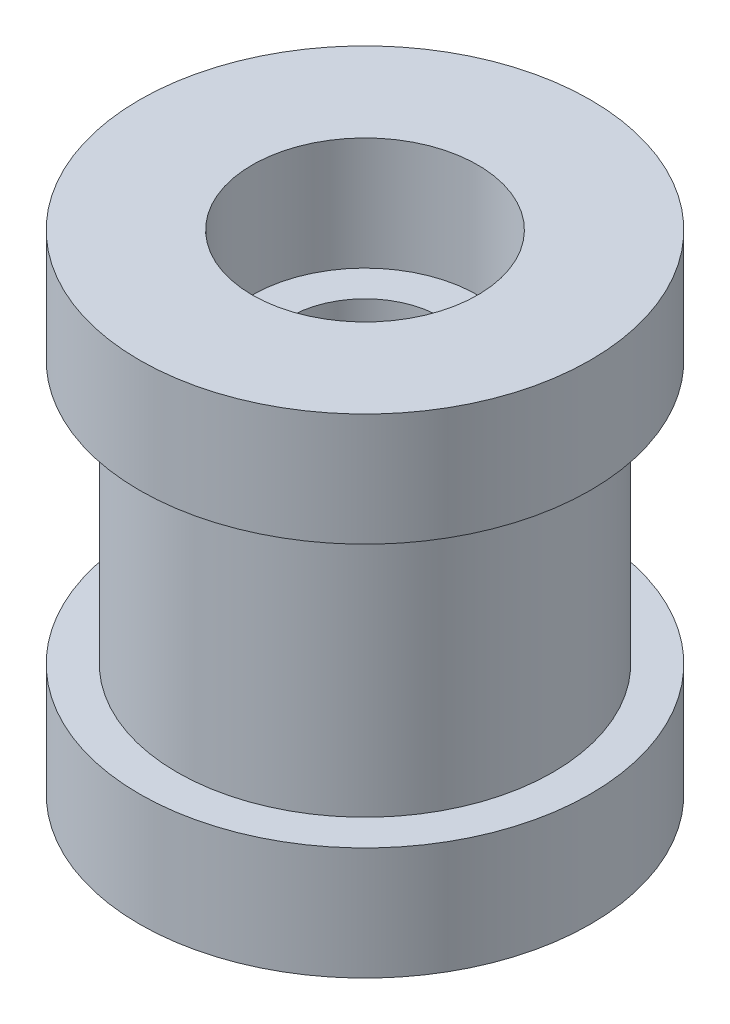
SolidWorks part; units mm, degrees
ref_plane "Front Plane" through (0, 0, 0) normal (0, 0, 1) x (1, 0, 0)
ref_plane "Top Plane" through (0, 0, 0) normal (0, 1, 0) x (1, 0, 0)
ref_plane "Right Plane" through (0, 0, 0) normal (1, 0, 0) x (0, 0, -1)
sketch "Sketch1" plane through (0, 0, 0) normal (0, 0, 1) x (1, 0, 0)
  line L0 (0, 78.4868) -> (0, -89.9219) construction
  line L1 (-60, 130) -> (-30, 130)
  line L2 (-30, 130) -> (-30, 100)
  line L3 (-30, 100) -> (-20, 100)
  line L4 (-20, 100) -> (-20, 85)
  line L5 (-20, 85) -> (-35, 85)
  line L6 (-35, 85) -> (-35, 45)
  line L7 (-35, 45) -> (-20, 45)
  line L8 (-20, 45) -> (-20, 30)
  line L9 (-20, 30) -> (-30, 30)
  line L10 (-30, 30) -> (-30, 0)
  line L11 (-30, 0) -> (-60, 0)
  line L12 (-60, 0) -> (-60, 30)
  line L13 (-60, 30) -> (-50, 30)
  line L14 (-50, 30) -> (-50, 100)
  line L15 (-50, 100) -> (-60, 100)
  line L16 (-60, 100) -> (-60, 130)
  line L17 (-110.7714, 0) -> (102.5534, 0) construction
  dimension "D1" = 130
  dimension "D2" = 10
  dimension "D3" = 30
  dimension "D4" = 70
  dimension "D5" = 15
  dimension "D6" = 40
  dimension "D7" = 30
  dimension "D8" = 10
  dimension "D9" = 15
  dimension "D10" = 60
revolve "Revolve4" add sketch "Sketch1" angle 360 about L0
